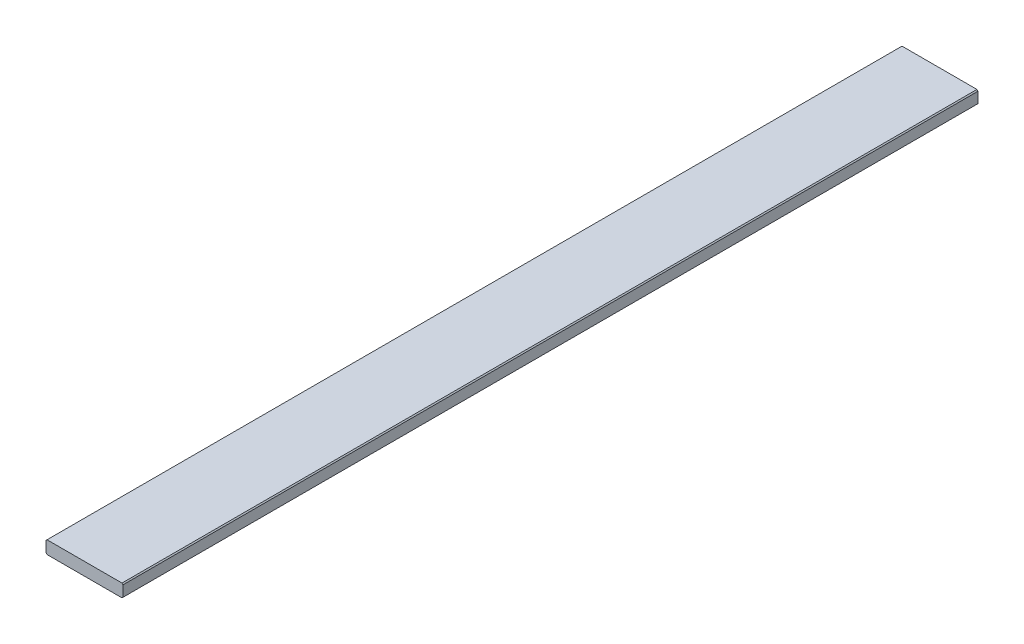
SolidWorks part; units mm, degrees
ref_plane "Спереди" through (0, 0, 0) normal (0, 0, 1) x (1, 0, 0)
ref_plane "Сверху" through (0, 0, 0) normal (0, 1, 0) x (1, 0, 0)
ref_plane "Справа" through (0, 0, 0) normal (1, 0, 0) x (0, 0, -1)
sketch "Эскиз1" plane through (0, 0, 0) normal (0, 0, 1) x (1, 0, 0)
  line L0 (-75, 10.5) -> (-73, 12.5)
  line L1 (-73, 12.5) -> (73, 12.5)
  line L2 (-75, 10.5) -> (-75, -10.5)
  line L3 (-73, -12.5) -> (73, -12.5)
  line L4 (75, 10.5) -> (75, -10.5)
  line L5 (-75, 12.5) -> (75, -12.5) construction
  line L6 (-75, -12.5) -> (75, 12.5) construction
  line L7 (-75, -10.5) -> (-73, -12.5)
  line L8 (73, -12.5) -> (75, -10.5)
  line L9 (73, 12.5) -> (75, 10.5)
  point P0 (0, 0)
  dimension "D1" = 150
  dimension "D2" = 25
extrude "Бобышка-Вытянуть1" add sketch "Эскиз1" along normal blind 1665
